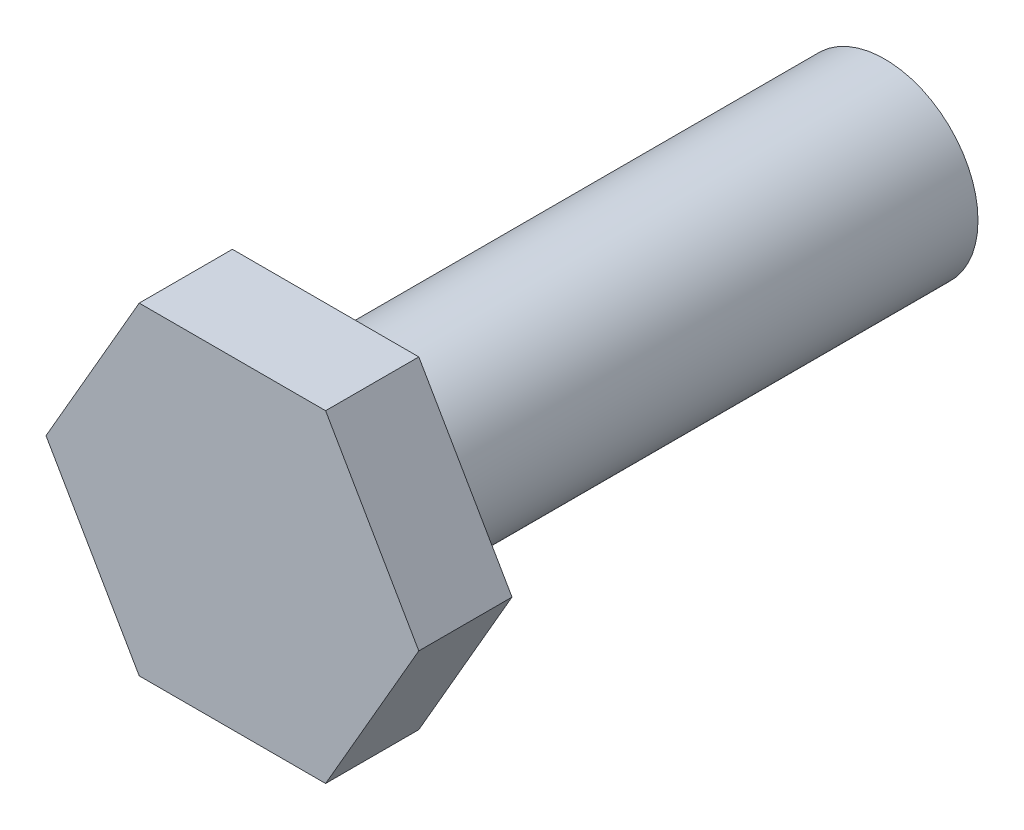
SolidWorks part; units mm, degrees
ref_plane "Front Plane" through (0, 0, 0) normal (0, 0, 1) x (1, 0, 0)
ref_plane "Top Plane" through (0, 0, 0) normal (0, 1, 0) x (1, 0, 0)
ref_plane "Right Plane" through (0, 0, 0) normal (1, 0, 0) x (0, 0, -1)
sketch "Sketch1" plane through (0, 0, 0) normal (0, 0, 1) x (1, 0, 0)
  circle A0 centre (0, 0) radius 5
  dimension "D1" = 10
extrude "Boss-Extrude1" add sketch "Sketch1" along normal blind 30
sketch "Sketch6" plane through (0, 0, 30) normal (0, 0, 1) x (1, 0, 0)
  line L1 (-10, 0) -> (-5, -8.6603)
  line L2 (-5, -8.6603) -> (5, -8.6603)
  line L3 (5, -8.6603) -> (10, 0)
  line L4 (10, 0) -> (5, 8.6603)
  line L5 (5, 8.6603) -> (-5, 8.6603)
  line L6 (-5, 8.6603) -> (-10, 0)
  circle A0 centre (0, 0) radius 10
  circle A1 centre (0, 0) radius 8.6603 construction
  circle M1 centre (0, 0) radius 5
extrude "Boss-Extrude3" add sketch "Sketch6" along normal blind 5 contours L5 L6 L1 L2 L3 L4 M1 | M1
equation "\"rs\"=10"
equation "\"D1@Sketch1\"=\"rs\""
equation "\"ls\" = 30"
equation "\"rl\"=23.3802"
equation "\"D1@Boss-Extrude1\"=\"ls\""
equation "\"ll\"=5"
